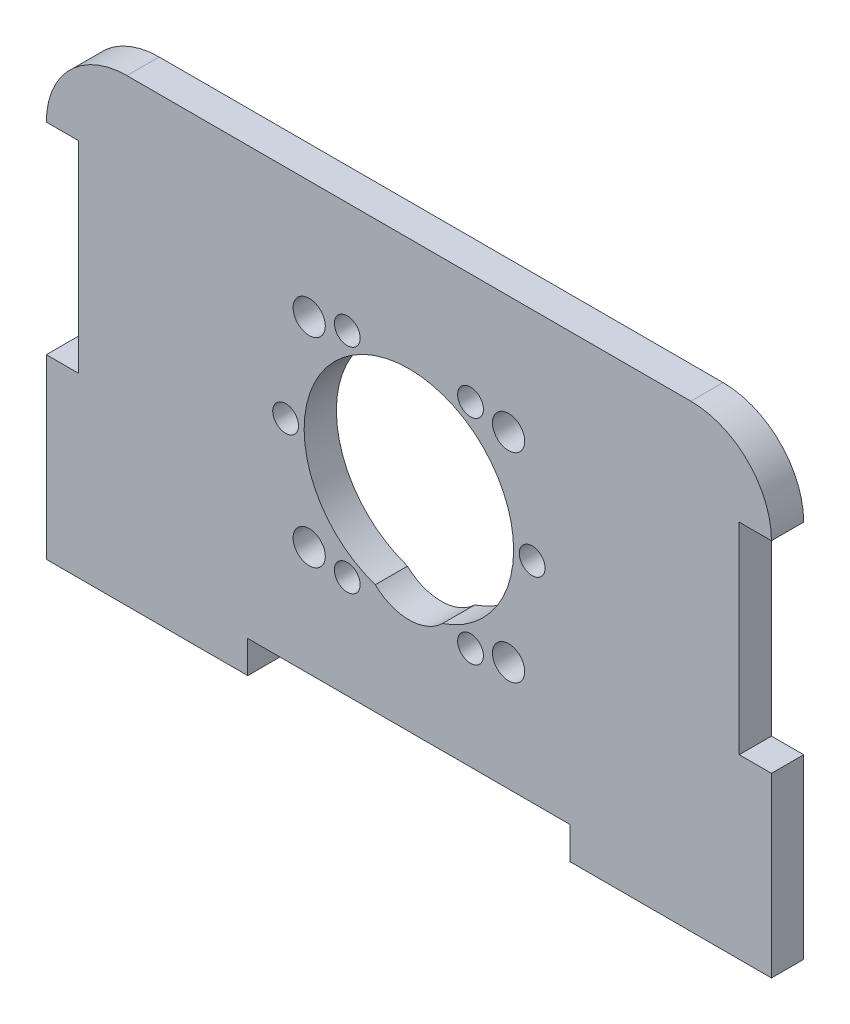
SolidWorks part; units mm, degrees
ref_plane "Front Plane" through (0, 0, 0) normal (0, 0, 1) x (1, 0, 0)
ref_plane "Top Plane" through (0, 0, 0) normal (0, 1, 0) x (1, 0, 0)
ref_plane "Right Plane" through (0, 0, 0) normal (1, 0, 0) x (0, 0, -1)
sketch "Sketch1" plane through (0, 0, 0) normal (0, 1, 0) x (1, 0, 0)
  line L1 (25, -2) -> (-25, -2)
  line L2 (25, -2) -> (25, 2)
  line L3 (25, 2) -> (-25, 2)
  line L4 (-25, -2) -> (-25, 2)
  line L5 (25, -2) -> (-25, 2) construction
  line L6 (25, 2) -> (-25, -2) construction
  point P0 (0, 0)
extrude "Boss-Extrude1" add sketch "Sketch1" along normal blind 50
sketch "Sketch2" plane through (0, 0, 2) normal (0, 0, 1) x (1, 0, 0)
  line L0 (-25, 0) -> (25, 0) construction
  circle A0 centre (0, 23) radius 13
  dimension "D1" = 23
extrude "Cut-Extrude1" cut sketch "Sketch2" against normal blind 50
sketch "Sketch4" plane through (0, 0, 2) normal (0, 0, 1) x (1, 0, 0)
  line L0 (0, 23) -> (12.3744, 35.3744) construction
  line L1 (-25, 0) -> (25, 0) construction
  line L2 (12.3744, 10.6256) -> (-12.3744, 35.3744) construction
  line L3 (0, 23) -> (-12.3744, 10.6256) construction
  circle A3 centre (0, 23) radius 17.5
  circle A7 centre (12.3744, 35.3744) radius 2
  circle A8 centre (12.3744, 10.6256) radius 2
  circle A9 centre (-12.3744, 35.3744) radius 2
  circle A10 centre (-12.3744, 10.6256) radius 2
  dimension "D1" = 45
extrude "Cut-Extrude3" cut sketch "Sketch4" against normal blind 50 contours A3 A9 | A3 A9 | A3 A7 | A3 A7 | A3 A8 | A3 A8 | A3 A10 | A3 A10
sketch "Sketch7" plane through (-25, 0, 0) normal (-1, 0, 0) x (0, 0, 1)
  line L1 (2, 50) -> (-2, 50)
  line L2 (2, 50) -> (2, 0)
  line L3 (2, 0) -> (-2, 0)
  line L4 (-2, 50) -> (-2, 0)
extrude "Boss-Extrude3" add sketch "Sketch7" along normal blind 20
mirror "Mirror1" about plane through (0, 0, 0) normal (1, 0, 0) of "Boss-Extrude3"
sketch "Sketch8" plane through (0, 0, 0) normal (0, -1, 0) x (1, 0, 0)
  line L1 (-45, 2) -> (45, 2)
  line L2 (-45, 2) -> (-45, -2)
  line L3 (-45, -2) -> (45, -2)
  line L4 (45, 2) -> (45, -2)
extrude "Boss-Extrude4" add sketch "Sketch8" along normal blind 3
sketch "Sketch9" plane through (0, 0, 2) normal (0, 0, 1) x (1, 0, 0)
  line L0 (0, -2.2) -> (0, 2.2) construction
  line L1 (-45, -3) -> (-20, -3)
  line L2 (-45, -3) -> (-45, -7)
  line L3 (-45, -7) -> (-20, -7)
  line L4 (-20, -3) -> (-20, -7)
  line L5 (20, -3) -> (20, -7)
  line L6 (45, -7) -> (20, -7)
  line L7 (45, -3) -> (45, -7)
  line L8 (45, -3) -> (20, -3)
  dimension "D1" = 4
  dimension "D2" = 25
extrude "Boss-Extrude5" add sketch "Sketch9" against normal blind 4
fillet "Fillet1" radius 10 2 edges at (-45, 50, 0) (45, 50, 0)
sketch "Sketch10" plane through (0, 0, 2) normal (0, 0, 1) x (1, 0, 0)
  circle A0 centre (0, 23) radius 15.3
  circle A1 centre (-15.3, 23) radius 1.6
extrude "Cut-Extrude4" cut sketch "Sketch10" against normal blind 20 contours A0 A1 | A0 A1
pattern_circular "CirPattern1" count 6 over 360 about axis through (0, 23, 0) along (0, 0, 1) of "Cut-Extrude4"
sketch "Sketch11" plane through (0, 0, 2) normal (0, 0, 1) x (1, 0, 0)
  circle A0 centre (0, 15) radius 6
  dimension "D1" = 15
extrude "Cut-Extrude5" cut sketch "Sketch11" against normal blind 20
sketch "Sketch12" plane through (0, 0, 2) normal (0, 0, 1) x (1, 0, 0)
  line L1 (45, 40) -> (41, 40)
  line L2 (45, 40) -> (45, 15)
  line L3 (45, 15) -> (41, 15)
  line L4 (41, 40) -> (41, 15)
  line L5 (0, -2.2) -> (0, 2.2) construction
  line L6 (-41, 40) -> (-41, 15)
  line L7 (-45, 15) -> (-41, 15)
  line L8 (-45, 40) -> (-45, 15)
  line L9 (-45, 40) -> (-41, 40)
  dimension "D1" = 4
  dimension "D2" = 25
extrude "Cut-Extrude6" cut sketch "Sketch12" against normal blind 20
